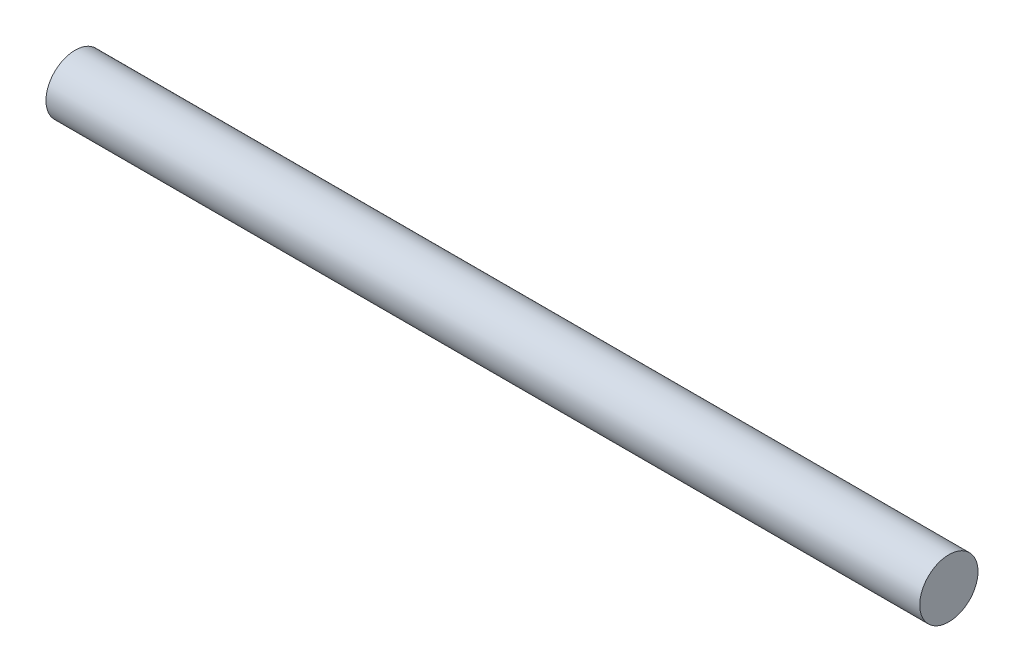
SolidWorks part; units mm, degrees
ref_plane "Front Plane" through (0, 0, 0) normal (0, 0, 1) x (1, 0, 0)
ref_plane "Top Plane" through (0, 0, 0) normal (0, 1, 0) x (1, 0, 0)
ref_plane "Right Plane" through (0, 0, 0) normal (1, 0, 0) x (0, 0, -1)
sketch "Sketch1" plane through (0, 0, 0) normal (1, 0, 0) x (0, 0, -1)
  circle A0 centre (0, 0) radius 4
  dimension "D1" = 8
extrude "Boss-Extrude1" add sketch "Sketch1" along normal blind 120
